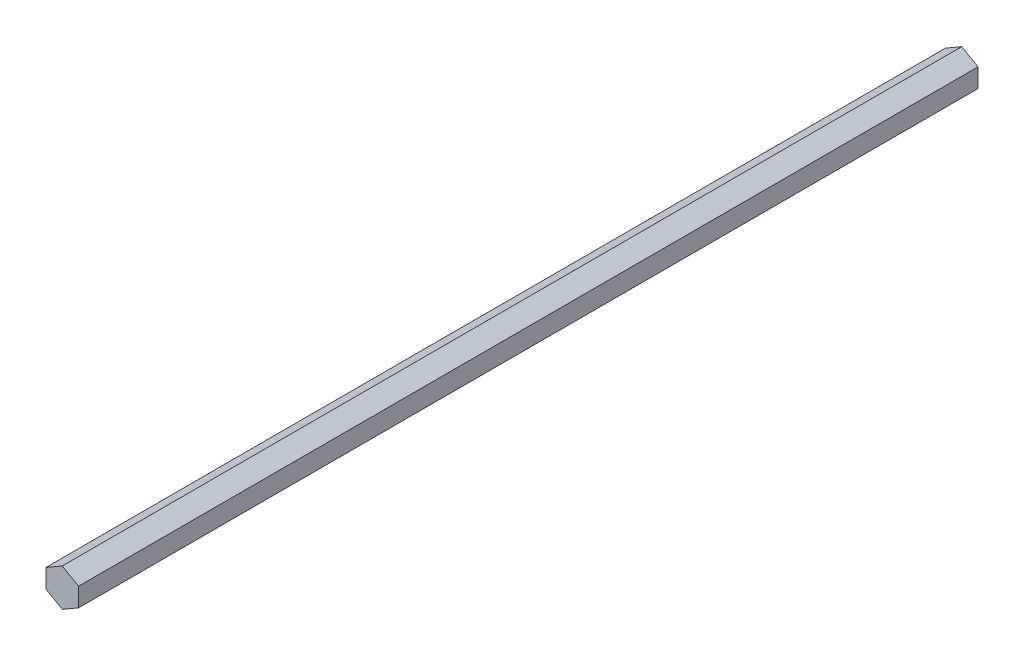
SolidWorks part; units mm, degrees
ref_plane "Front Plane" through (0, 0, 0) normal (0, 0, 1) x (1, 0, 0)
ref_plane "Top Plane" through (0, 0, 0) normal (0, 1, 0) x (1, 0, 0)
ref_plane "Right Plane" through (0, 0, 0) normal (1, 0, 0) x (0, 0, -1)
sketch "Sketch1" plane through (0, 0, 0) normal (0, 0, 1) x (1, 0, 0)
  line L1 (0, 7.3323) -> (-6.35, 3.6662) construction
  line L2 (-6.35, 3.6662) -> (-6.35, -3.6662) construction
  line L3 (-6.35, -3.6662) -> (0, -7.3323) construction
  line L4 (0, -7.3323) -> (6.35, -3.6662) construction
  line L5 (6.35, -3.6662) -> (6.35, 3.6662) construction
  line L6 (6.35, 3.6662) -> (0, 7.3323) construction
  circle A2 centre (0, 0) radius 6.35 construction
  dimension "Width" = 12.7
sketch "Sketch2" plane through (0, 0, 0) normal (1, 0, 0) x (0, 0, -1)
  line L0 (-152.4, 7.3323) -> (152.4, 7.3323) construction
  point P2 (0, 7.3323)
  point P3 (120.65, 7.3323)
  point P4 (-120.65, 7.3323)
  dimension "Length" = 304.8
  dimension "D2" = 31.75
  dimension "D1" = 31.75
sketch "Sketch3" plane through (0, 0, 0) normal (0, 0, 1) x (1, 0, 0)
  line L0 (-6.35, -3.6662) -> (0, -7.3323) construction
  line L1 (0, -7.3323) -> (6.35, -3.6662) construction
  line L2 (6.35, -3.6662) -> (6.35, 3.6662) construction
  line L3 (6.35, 3.6662) -> (0, 7.3323) construction
  line L4 (0, 7.3323) -> (-6.35, 3.6662) construction
  line L5 (-6.35, 3.6662) -> (-6.35, -3.6662) construction
  line L6 (-6.35, -3.6662) -> (0, -7.3323)
  line L7 (0, -7.3323) -> (6.35, -3.6662)
  line L8 (6.35, -3.6662) -> (6.35, 3.6662)
  line L9 (6.35, 3.6662) -> (0, 7.3323)
  line L10 (0, 7.3323) -> (-6.35, 3.6662)
  line L11 (-6.35, 3.6662) -> (-6.35, -3.6662)
extrude "Boss-Extrude2" add sketch "Sketch3" along normal up to vertex (152.4 mm away) and the other way up to vertex (152.4 mm away) up to point (0, 7.3323, 152.4) other way up to point (0, 7.3323, -152.4)
sketch "Sketch4" plane through (0, 0, 152.4) normal (0, 0, 1) x (1, 0, 0)
  line L6 (-6.35, 3.6662) -> (-6.35, -3.6662)
  line L7 (-6.35, -3.6662) -> (0, -7.3323)
  line L8 (0, -7.3323) -> (6.35, -3.6662)
  line L9 (6.35, -3.6662) -> (6.35, 3.6662)
  line L10 (6.35, 3.6662) -> (0, 7.3323)
  line L11 (0, 7.3323) -> (-6.35, 3.6662)
  line L12 (-6.35, 3.6662) -> (-6.35, -3.6662)
  line L13 (-6.35, -3.6662) -> (0, -7.3323)
  line L14 (0, -7.3323) -> (6.35, -3.6662)
  line L15 (6.35, -3.6662) -> (6.35, 3.6662)
  line L16 (6.35, 3.6662) -> (0, 7.3323)
  line L17 (0, 7.3323) -> (-6.35, 3.6662)
  dimension "D1" = 0
extrude "Boss-Extrude3" add sketch "Sketch4" along normal blind 46.228
equation "\"D2@Sketch2\" = \"D1@Sketch2\""
equation "\"D1@Sketch2\" = \"Width@Sketch1\" * 2.5"
